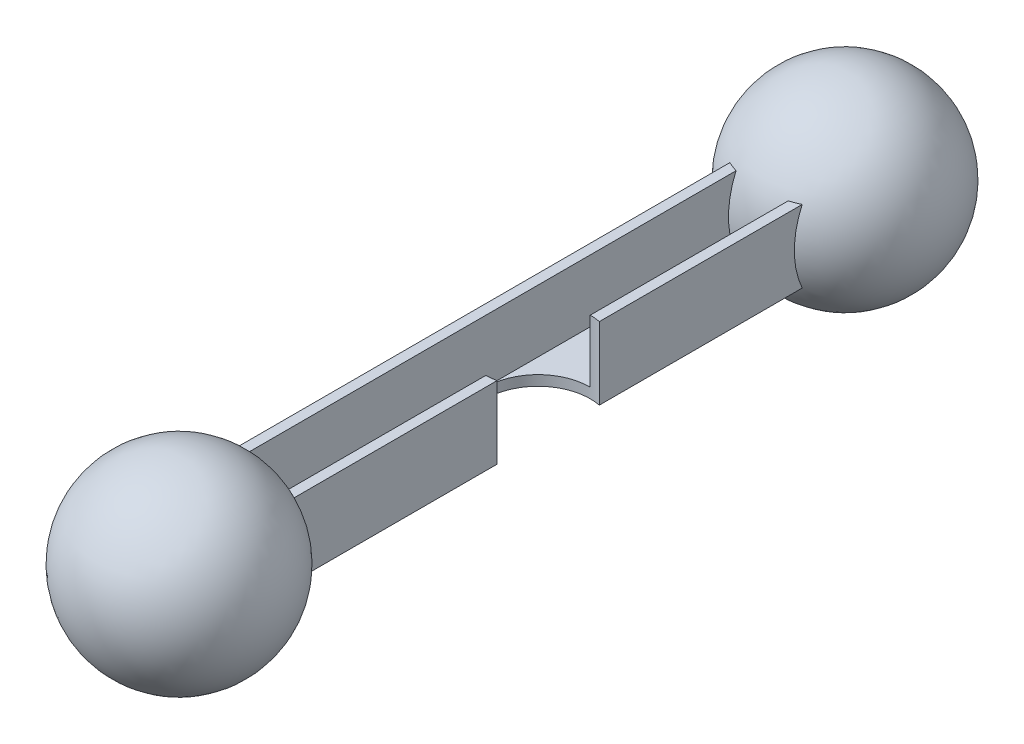
SolidWorks part; units mm, degrees
ref_plane "Front" through (0, 0, 0) normal (0, 0, 1) x (1, 0, 0)
ref_plane "Top" through (0, 0, 0) normal (0, 1, 0) x (1, 0, 0)
ref_plane "Right" through (0, 0, 0) normal (1, 0, 0) x (0, 0, -1)
sketch "Sketch1" plane through (0, 0, 0) normal (0, 0, 1) x (1, 0, 0)
  line L0 (-9.0093, 12.5) -> (-9.0093, -9.0093)
  line L1 (-12.5, 12.5) -> (-9.0093, 12.5)
  line L2 (-12.5, 12.5) -> (-12.5, -12.5)
  line L3 (-12.5, -12.5) -> (12.5, -12.5)
  line L4 (12.5, 12.5) -> (12.5, -12.5)
  line L5 (-12.5, 12.5) -> (12.5, -12.5) construction
  line L6 (-12.5, -12.5) -> (12.5, 12.5) construction
  line L7 (-9.0093, -9.0093) -> (9.0093, -9.0093)
  line L8 (9.0093, -9.0093) -> (9.0093, 12.5)
  line L9 (9.0093, 12.5) -> (12.5, 12.5)
  point P0 (0, 0)
  dimension "D1" = 25
  dimension "D2" = 25
extrude "Boss-Extrude1" add sketch "Sketch1" along normal mid plane 230 contours L2 L3 L4 L9 L8 L7 L0 L1
sketch "Sketch2" plane through (0, -9.0093, 0) normal (0, 1, 0) x (1, 0, 0)
  line L1 (-9.0093, -115) -> (-9.0093, 115) construction
  circle A0 centre (8.9907, 0) radius 18
  dimension "D1" = 18
  dimension "D2" = 36
extrude "Cut-Extrude1" cut sketch "Sketch2" against normal through all both and the other way through all
sketch "Sketch3" plane through (0, 0, 115) normal (0, 0, 1) x (1, 0, 0)
  line L0 (0, 32.5) -> (0, -32.5)
  arc A0 (0, -32.5) -> (0, 32.5) centre (0, 0) ccw
revolve "Revolve1" add sketch "Sketch3" angle 360 about L0
mirror "Mirror1" about plane through (0, 0, 0) normal (0, 0, 1) of "Revolve1"
